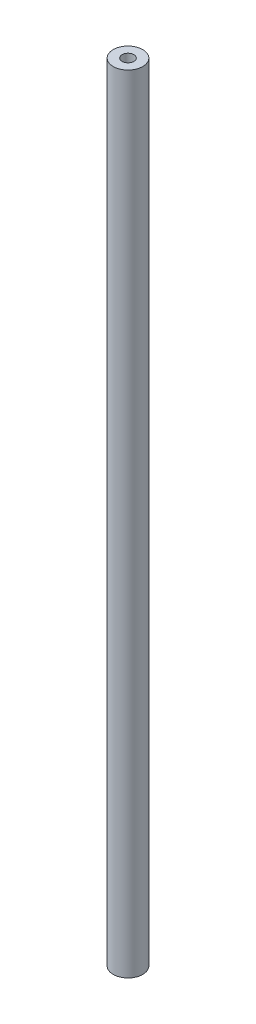
SolidWorks part; units mm, degrees
ref_plane "前视基准面" through (0, 0, 0) normal (0, 0, 1) x (1, 0, 0)
ref_plane "上视基准面" through (0, 0, 0) normal (0, 1, 0) x (1, 0, 0)
ref_plane "右视基准面" through (0, 0, 0) normal (1, 0, 0) x (0, 0, -1)
sketch "草图1" plane through (0, 0, 0) normal (0, 1, 0) x (1, 0, 0)
  circle A0 centre (0, 0) radius 7.5
  dimension "D1" = 15
extrude "凸台-拉伸1" add sketch "草图1" along normal blind 400
sketch "草图2" plane through (0, 400, 0) normal (0, 1, 0) x (1, 0, 0)
  circle A0 centre (0, 0) radius 3
  dimension "D1" = 6
extrude "切除-拉伸1" cut sketch "草图2" against normal blind 20
sketch "草图3" plane through (0, 0, 0) normal (0, -1, 0) x (-1, 0, 0)
  circle A0 centre (0, 0) radius 3
  dimension "D1" = 6
extrude "切除-拉伸2" cut sketch "草图3" against normal blind 20
sketch3d "URDF Reference"
  line L0 (0, 0, 0) -> (10, 0, 0) construction
  line L1 (0, 0, 0) -> (0, 0, -10) construction
  point P0 (0, 0, 0)
